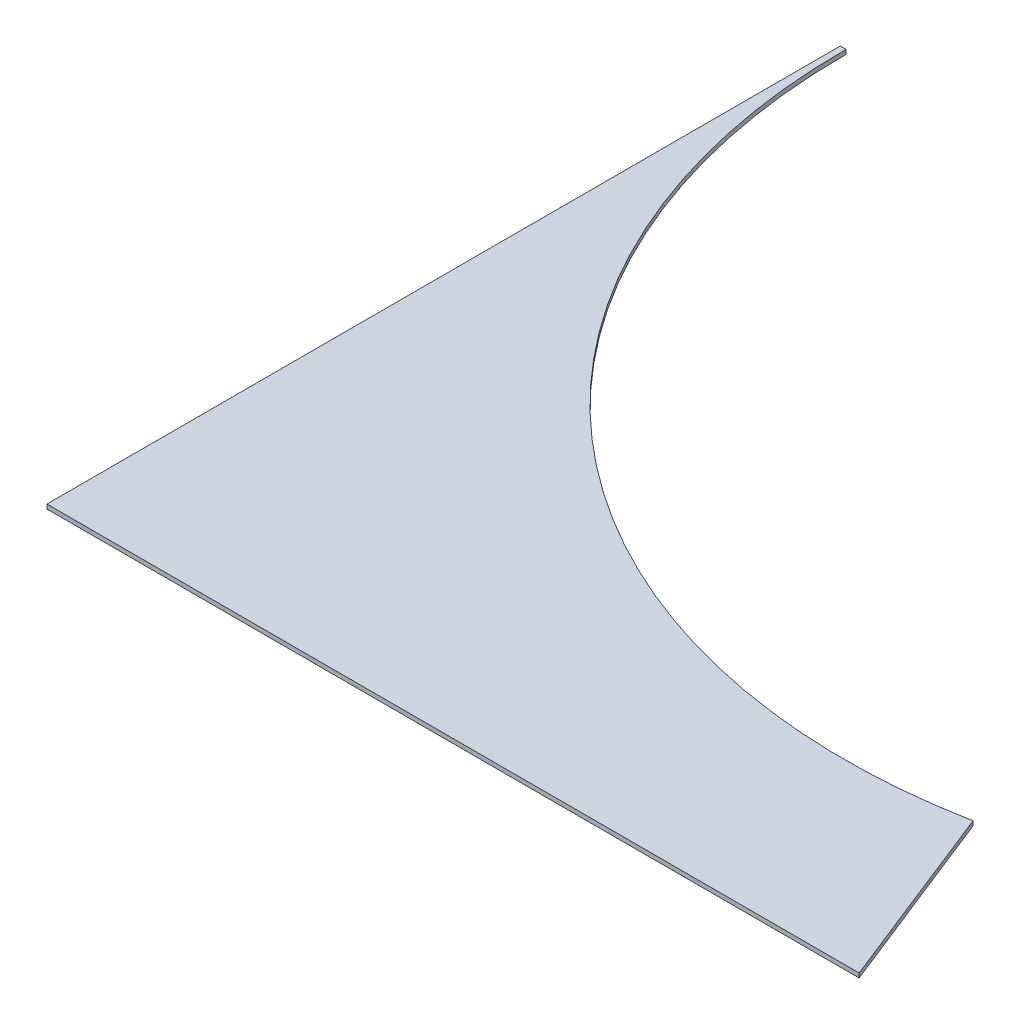
SolidWorks part; units mm, degrees
material "ASTM A36 Steel"
ref_plane "Front Plane" through (0, 0, 0) normal (0, 0, 1) x (1, 0, 0)
ref_plane "Top Plane" through (0, 0, 0) normal (0, 1, 0) x (1, 0, 0)
ref_plane "Right Plane" through (0, 0, 0) normal (1, 0, 0) x (0, 0, -1)
sketch "Sketch1" plane through (0, 0, 0) normal (0, 1, 0) x (1, 0, 0)
  line L5 (281, -416.84) -> (332.5962, -546.9854)
  line L6 (-227.4038, -546.9854) -> (332.5962, -546.9854)
  line L7 (-223.4038, 0) -> (-227.4038, 0)
  line L8 (-227.4038, 0) -> (-227.4038, -546.9854)
  arc A2 (-223.4038, 0) -> (281, -416.84) centre (200.0947, -1.1398) ccw
  dimension "D3" = 847
  dimension "D6" = 281
  dimension "D1" = 547
  dimension "D2" = 140
  dimension "D4" = 560
  dimension "D5" = 4
extrude "Boss-Extrude1" add sketch "Sketch1" along normal blind 3
